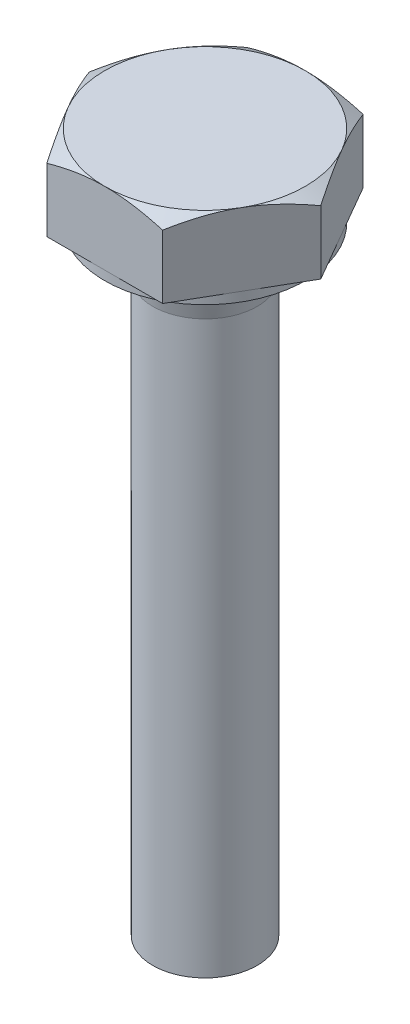
SolidWorks part; units mm, degrees
ref_plane "Vorderseite" through (0, 0, 0) normal (0, 0, 1) x (1, 0, 0)
ref_plane "Oben" through (0, 0, 0) normal (0, 1, 0) x (1, 0, 0)
ref_plane "Rechts" through (0, 0, 0) normal (1, 0, 0) x (0, 0, -1)
sketch "Skizze1" plane through (0, 0, 0) normal (0, 0, 1) x (1, 0, 0)
  line L0 (0, 5.3) -> (0, -40)
  line L1 (0, 5.3) -> (6.5, 5.3)
  line L2 (6.5, 5.3) -> (7.5055, 4.7195)
  line L3 (7.5055, 4.7195) -> (7.5055, 0.6)
  line L4 (7.5055, 0.6) -> (6.5, 0.6)
  line L5 (6.5, 0.6) -> (6.5, 0)
  line L6 (6.5, 0) -> (4, 0)
  line L7 (4, 0) -> (4, -0.002)
  line L8 (3.998, -0.002) -> (3.3865, -3)
  line L9 (3.3865, -3) -> (3.3865, -40)
  line L10 (3.3865, -40) -> (0, -40)
  line L11 (0, 5.3) -> (0, -40) construction
  line L12 (4, -0.002) -> (3.998, -0.002)
  dimension "D1" = 0.002
  dimension "D2" = 0.002
  dimension "C" = 0.6
  dimension "K" = 5.3
  dimension "D3" = 30
  dimension "E" = 15.011
  dimension "DK" = 6.773
  dimension "DG" = 8
  dimension "A" = 3
  dimension "L" = 40
revolve "Basis-Rotation" add sketch "Skizze1" angle 360 about L11
sketch "Skizze2" plane through (0, 5.3, 0) normal (0, 1, 0) x (-1, 0, 0)
  line L0 (-7.5056, 0) -> (7.5056, 0) construction
  line L1 (0, 6.5) -> (0, -6.5) construction
  line L2 (-3.7528, 6.5) -> (3.7528, 6.5)
  line L3 (3.7528, 6.5) -> (7.5056, 0)
  line L4 (-3.7528, 6.5) -> (-7.5056, 0)
  line L5 (-3.7528, -6.5) -> (-7.5056, 0)
  line L6 (3.7528, -6.5) -> (7.5056, 0)
  line L7 (-3.7528, -6.5) -> (3.7528, -6.5)
  point P10 (0, 6.5)
  point P12 (0, -6.5)
  dimension "D1" = 120
extrude "Schnitt-Linear austragen1" cut sketch "Skizze2" against normal through all flip side to cut
